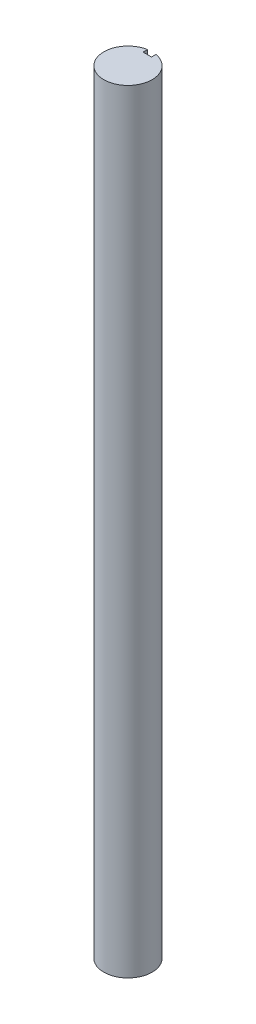
SolidWorks part; units mm, degrees
ref_plane "Front Plane" through (0, 0, 0) normal (0, 0, 1) x (1, 0, 0)
ref_plane "Top Plane" through (0, 0, 0) normal (0, 1, 0) x (1, 0, 0)
ref_plane "Right Plane" through (0, 0, 0) normal (1, 0, 0) x (0, 0, -1)
sketch "Sketch1" plane through (0, 0, 0) normal (0, 1, 0) x (1, 0, 0)
  circle A0 centre (0, 0) radius 10
  dimension "D1" = 20
extrude "Boss-Extrude1" add sketch "Sketch1" along normal mid plane 320
sketch "Sketch2" plane through (0, 160, 0) normal (0, 1, 0) x (1, 0, 0)
  line L0 (0, 0) -> (0, 10) construction
  line L1 (-1.75, 9.8457) -> (-1.75, 8)
  line L2 (-1.75, 8) -> (1.75, 8)
  line L3 (1.75, 8) -> (1.75, 9.8457)
  line L4 (-1.75, 9.8457) -> (-1.75, 11.1473)
  line L5 (-1.75, 11.1473) -> (1.75, 11.1473)
  line L6 (1.75, 11.1473) -> (1.75, 9.8457)
  circle A0 centre (0, 0) radius 10 construction
  dimension "D1" = 3.5
  dimension "D2" = 2
extrude "Cut-Extrude1" cut sketch "Sketch2" against normal blind 40
